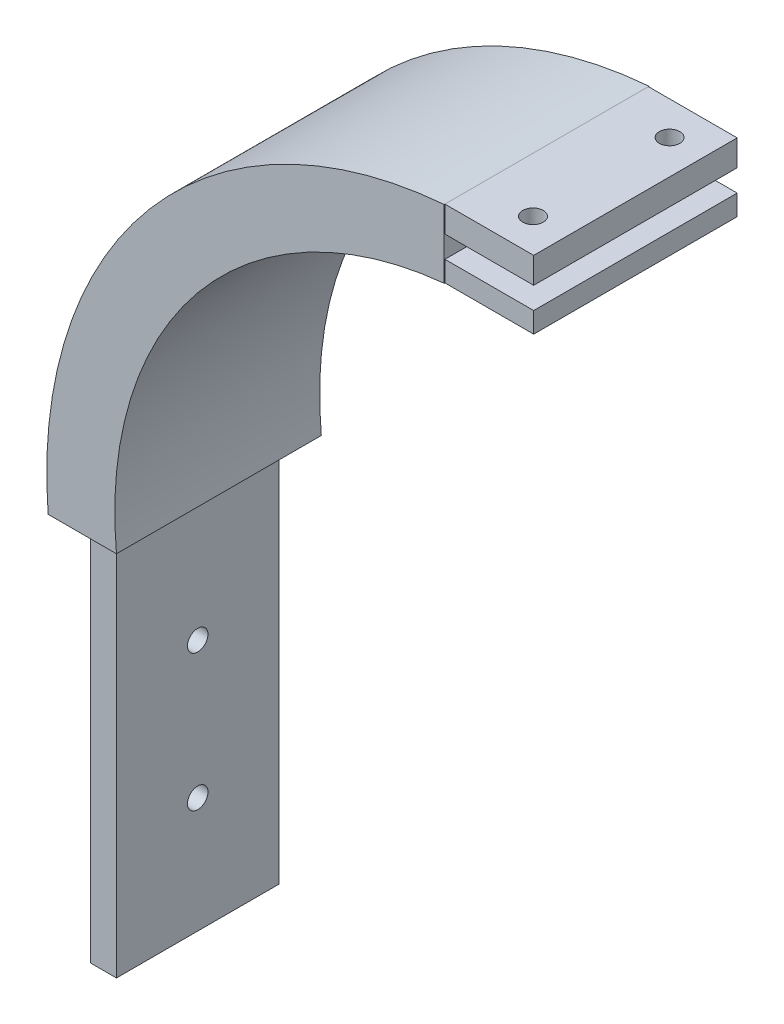
SolidWorks part; units mm, degrees
ref_plane "Front Plane" through (0, 0, 0) normal (0, 0, 1) x (1, 0, 0)
ref_plane "Top Plane" through (0, 0, 0) normal (0, 1, 0) x (1, 0, 0)
ref_plane "Right Plane" through (0, 0, 0) normal (1, 0, 0) x (0, 0, -1)
sketch "Sketch1" plane through (0, 0, 0) normal (0, 0, 1) x (1, 0, 0)
  line L0 (-10, 0) -> (0, 0)
  line L1 (48, 58.3) -> (48, 68.3)
  arc A0 (0, 0) -> (48, 58.3) centre (53.15, 5.15) cw
  arc A1 (48, 68.3) -> (-10, 0) centre (53.15, 5.15) ccw
  dimension "D1" = 58.3
  dimension "D3" = 10
  dimension "D2" = 48
  dimension "D4" = 10
extrude "Boss-Extrude1" add sketch "Sketch1" along normal mid plane 30
sketch "Sketch2" plane through (0, 0, 0) normal (0, -1, 0) x (1, 0, 0)
  line L0 (-6.9, 11.9) -> (-6.9, -11.9)
  line L1 (-6.9, -11.9) -> (-3.1, -11.9)
  line L2 (-3.1, -11.9) -> (-3.1, 11.9)
  line L3 (-3.1, 11.9) -> (-6.9, 11.9)
  line L4 (-10, 15) -> (-10, -15) construction
  line L5 (-10, 15) -> (0, 15) construction
  line L6 (0, 15) -> (0, -15) construction
  line L7 (-10, -15) -> (0, -15) construction
  dimension "D1" = 3.1
  dimension "D2" = 3.1
  dimension "D3" = 3.1
  dimension "D4" = 3.1
extrude "Boss-Extrude2" add sketch "Sketch2" along normal blind 56.9
sketch "Sketch3" plane through (-6.9, 0, 0) normal (-1, 0, 0) x (0, 0, 1)
  line L0 (0, 0) -> (0, -20) construction
  line L1 (0, -20) -> (0, -40) construction
  circle A0 centre (0, -20) radius 1.5
  circle A1 centre (0, -40) radius 1.5
  dimension "D1" = 3
  dimension "D2" = 3
  dimension "D3" = 20
extrude "Cut-Extrude1" cut sketch "Sketch3" against normal up to surface (3.8 mm away) up to face at (-3.1, -28.45, 0)
sketch "Sketch4" plane through (48, 0, 0) normal (1, 0, 0) x (0, 0, -1)
  line L0 (-15, 68.3) -> (-15, 64.5)
  line L1 (-15, 58.3) -> (-15, 68.3) construction
  line L2 (-15, 64.5) -> (15, 64.5)
  line L3 (15, 58.3) -> (15, 68.3) construction
  line L4 (15, 64.5) -> (15, 68.3)
  line L5 (15, 68.3) -> (-15, 68.3)
  line L6 (-15, 58.3) -> (-15, 61.3)
  line L7 (-15, 61.3) -> (15, 61.3)
  line L8 (15, 61.3) -> (15, 58.3)
  line L9 (15, 58.3) -> (-15, 58.3)
  dimension "D1" = 3
  dimension "D2" = 3.8
extrude "Boss-Extrude3" add sketch "Sketch4" along normal blind 13
sketch "Sketch5" plane through (0, 58.3, 0) normal (0, -1, 0) x (1, 0, 0)
  line L0 (56, 15) -> (56, 10) construction
  line L2 (56, 10) -> (56, -10) construction
  line L3 (56, -10) -> (56, -15) construction
  line L5 (61, 15) -> (61, -15) construction
  line L6 (61, 15) -> (48, 15) construction
  line L7 (61, -15) -> (48, -15) construction
  circle A0 centre (56, 10) radius 1.5
  circle A1 centre (56, -10) radius 1.5
  dimension "D2" = 3
  dimension "D1" = 20
  dimension "D3" = 5
extrude "Cut-Extrude2" cut sketch "Sketch5" against normal up to surface (10 mm away) up to face at (54.5, 68.3, 0)
sketch "Sketch6" plane through (61, 0, 0) normal (1, 0, 0) x (0, 0, -1)
  line L0 (-15, 68.3) -> (-15, 58.3)
  line L1 (-15, 58.3) -> (-14.9, 58.3)
  line L2 (-15, 58.3) -> (15, 58.3) construction
  line L3 (-14.9, 58.3) -> (-14.9, 68.3)
  line L4 (15, 68.3) -> (-15, 68.3) construction
  line L5 (-14.9, 68.3) -> (-15, 68.3)
  line L6 (15, 68.3) -> (15, 58.3)
  line L7 (15, 58.3) -> (14.9, 58.3)
  line L8 (-15, 58.3) -> (15, 58.3) construction
  line L9 (14.9, 58.3) -> (14.9, 68.3)
  line L10 (14.9, 68.3) -> (15, 68.3)
  dimension "D1" = 0.1
extrude "Cut-Extrude3" cut sketch "Sketch6" against normal up to surface (13 mm away) up to face at (48, 62.9, 0)
